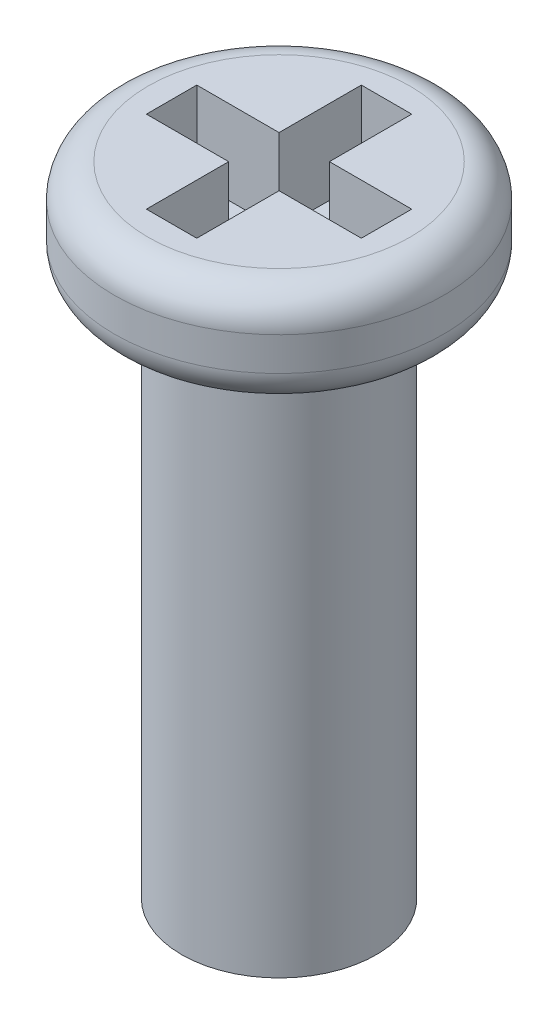
SolidWorks part; units mm, degrees
ref_plane "Front Plane" through (0, 0, 0) normal (0, 0, 1) x (1, 0, 0)
ref_plane "Top Plane" through (0, 0, 0) normal (0, 1, 0) x (1, 0, 0)
ref_plane "Right Plane" through (0, 0, 0) normal (1, 0, 0) x (0, 0, -1)
sketch "Sketch1" plane through (0, 0, 0) normal (0, 1, 0) x (1, 0, 0)
  circle A0 centre (0, 0) radius 1.45
  dimension "D1" = 2.9
extrude "Boss-Extrude1" add sketch "Sketch1" along normal blind 8
sketch "Sketch2" plane through (0, 8, 0) normal (0, 1, 0) x (1, 0, 0)
  circle A0 centre (0, 0) radius 2.45
  dimension "D1" = 4.9
extrude "Boss-Extrude2" add sketch "Sketch2" along normal blind 1.5
fillet "Fillet1" radius 0.5 2 edges at (0, 8, 2.45) (0, 9.5, 2.45)
sketch "Sketch3" plane through (0, 9.5, 0) normal (0, 1, 0) x (1, 0, 0)
  line L1 (-0.375, 1.6) -> (0.375, 1.6)
  line L2 (-0.375, 1.6) -> (-0.375, -1.6)
  line L3 (-0.375, -1.6) -> (0.375, -1.6)
  line L4 (0.375, 1.6) -> (0.375, -1.6)
  line L5 (-1.6, 0.375) -> (1.6, 0.375)
  line L6 (-1.6, 0.375) -> (-1.6, -0.375)
  line L7 (-1.6, -0.375) -> (1.6, -0.375)
  line L8 (1.6, 0.375) -> (1.6, -0.375)
  dimension "D1" = 0.75
  dimension "D2" = 0.75
  dimension "D3" = 3.2
  dimension "D4" = 3.2
  dimension "D5" = 1.6
  dimension "D6" = 0.375
  dimension "D7" = 1.6
  dimension "D8" = 0.375
extrude "Cut-Extrude1" cut sketch "Sketch3" against normal blind 1.25 contours L2 L5 L4 L1 | L2 L7 L4 L5 | L7 L2 L3 L4 | L8 L5 L4 L7 | L6 L7 L2 L5
fillet "Fillet4" radius 0.5 4 edges at (0, 8.25, 1.6) (1.6, 8.25, 0) (-1.6, 8.25, 0) (0, 8.25, -1.6)
